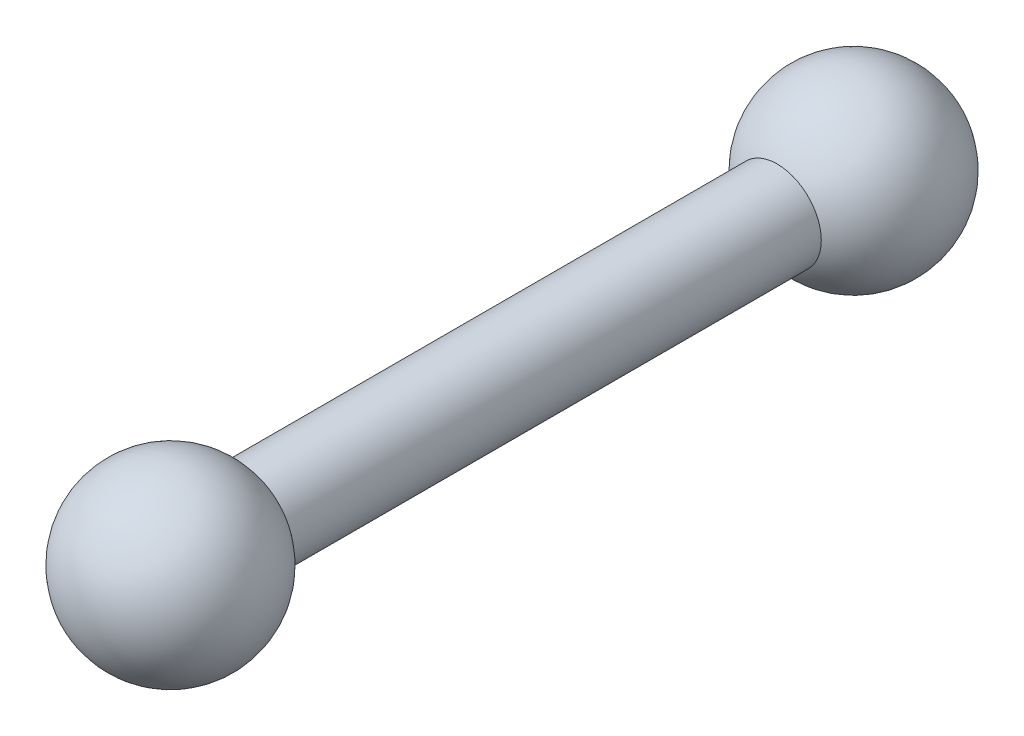
SolidWorks part; units mm, degrees
ref_plane "Front Plane" through (0, 0, 0) normal (0, 0, 1) x (1, 0, 0)
ref_plane "Top Plane" through (0, 0, 0) normal (0, 1, 0) x (1, 0, 0)
ref_plane "Right Plane" through (0, 0, 0) normal (1, 0, 0) x (0, 0, -1)
sketch "Sketch1" plane through (0, 0, 0) normal (0, 0, 1) x (1, 0, 0)
  circle A0 centre (0, 0) radius 2
  dimension "D1" = 4
extrude "Boss-Extrude1" add sketch "Sketch1" against normal blind 25
ref_plane "Plane1" through (0, 0, 3) normal (0, 0, 1) x (1, 0, 0)
sketch "Sketch2" plane through (0, 0, 3) normal (0, 0, 1) x (1, 0, 0)
  line L0 (0, 4) -> (0, -4) construction
  line L1 (0, 4) -> (0, -4)
  arc A1 (0, -4) -> (0, 4) centre (0, 0) ccw
  dimension "D1" = 8
revolve "Revolve1" add sketch "Sketch2" angle 360 about L0
ref_plane "Plane2" through (0, 0, -12.5) normal (0, 0, 1) x (1, 0, 0)
mirror "Mirror1" about plane through (0, 0, -12.5) normal (0, 0, 1) of "Revolve1"
